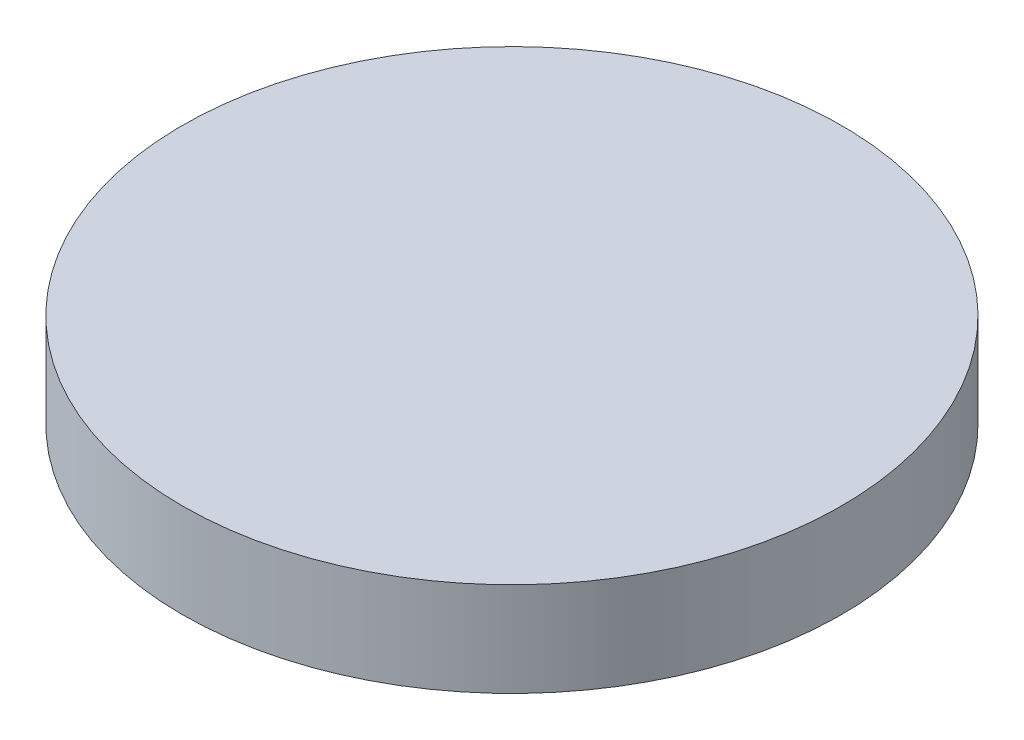
SolidWorks part; units mm, degrees
ref_plane "前视基准面" through (0, 0, 0) normal (0, 0, 1) x (1, 0, 0)
ref_plane "上视基准面" through (0, 0, 0) normal (0, 1, 0) x (1, 0, 0)
ref_plane "右视基准面" through (0, 0, 0) normal (1, 0, 0) x (0, 0, -1)
other "Configuration Table"
sketch "Sketch1" plane through (0, 0, 0) normal (1, 0, 0) x (0, 0, -1)
  line L0 (0, 0) -> (0, -3.297) construction
  line L1 (4.5, 0) -> (4.5, 3)
  line L2 (4.5, 3) -> (10.5, 3)
  line L3 (10.5, 3) -> (10.5, 6)
  line L4 (10.5, 6) -> (0, 6)
  line L5 (3, 3) -> (3, 0)
  line L6 (3, 3) -> (4.5, 3)
  line L7 (3, 0) -> (4.5, 0)
  line L8 (3, 3) -> (0, 3)
  line L9 (0, 6) -> (0, 3)
  dimension "D1" = 3
  dimension "D2" = 10.5
  dimension "D3" = 3
  dimension "D4" = 3
  dimension "D5" = 4.5
revolve "Revolve1" add sketch "Sketch1" angle 360 about L0
